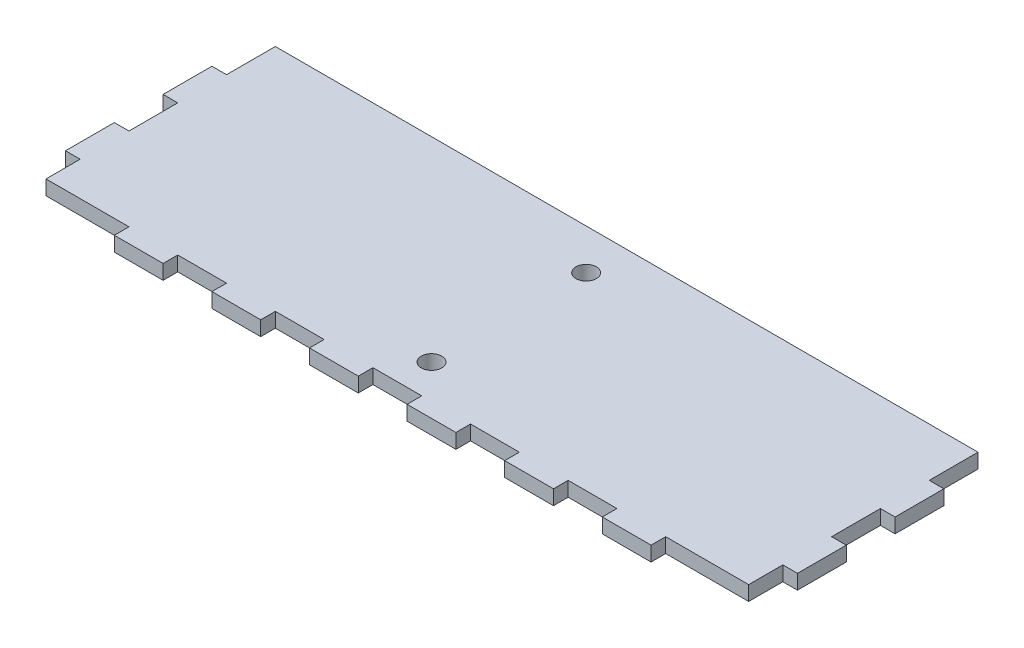
SolidWorks part; units mm, degrees
ref_plane "Plano frontal" through (0, 0, 0) normal (0, 0, 1) x (1, 0, 0)
ref_plane "Plano superior" through (0, 0, 0) normal (0, 1, 0) x (1, 0, 0)
ref_plane "Plano direito" through (0, 0, 0) normal (1, 0, 0) x (0, 0, -1)
sketch "mdfEsb" plane through (0, 0, 0) normal (0, 1, 0) x (1, 0, 0)
  line L1 (0, 0) -> (150, 0)
  line L2 (0, 0) -> (0, 50)
  line L3 (0, 50) -> (150, 50)
  line L4 (150, 0) -> (150, 50)
  dimension "D1" = 150
  dimension "D2" = 50
extrude "mdf" add sketch "mdfEsb" along normal blind 3
sketch "encaixeEsb" plane through (0, 3, 0) normal (0, 1, 0) x (1, 0, 0)
  line L0 (0, 0) -> (150, 0) construction
  line L1 (0, 0) -> (20, 0)
  line L2 (0, 0) -> (0, 3)
  line L4 (20, 0) -> (20, 3)
  line L5 (150, 0) -> (130, 0)
  line L6 (150, 0) -> (150, 3)
  line L8 (130, 0) -> (130, 3)
  line L9 (30, 0) -> (40, 0)
  line L10 (30, 0) -> (30, 3)
  line L11 (30, 3) -> (40, 3)
  line L12 (40, 0) -> (40, 3)
  line L13 (50, 0) -> (50, 3)
  line L14 (50, 0) -> (60, 0)
  line L15 (60, 0) -> (60, 3)
  line L16 (50, 3) -> (60, 3)
  line L17 (70, 0) -> (70, 3)
  line L18 (70, 0) -> (80, 0)
  line L19 (80, 0) -> (80, 3)
  line L20 (70, 3) -> (80, 3)
  line L21 (90, 0) -> (90, 3)
  line L22 (90, 0) -> (100, 0)
  line L23 (100, 0) -> (100, 3)
  line L24 (90, 3) -> (100, 3)
  line L25 (110, 0) -> (110, 3)
  line L26 (110, 0) -> (120, 0)
  line L27 (120, 0) -> (120, 3)
  line L28 (110, 3) -> (120, 3)
  line L29 (30, 0) -> (50, 0) construction
  line L30 (0, 50) -> (0, 0) construction
  line L31 (0, 20) -> (3, 20)
  line L32 (0, 20) -> (0, 30)
  line L33 (0, 30) -> (3, 30)
  line L34 (3, 20) -> (3, 30)
  line L35 (0, 40) -> (0, 50)
  line L36 (0, 40) -> (3, 40)
  line L37 (3, 40) -> (3, 50)
  line L38 (0, 50) -> (3, 50)
  line L39 (0, 60) -> (0, 70)
  line L40 (0, 60) -> (3, 60)
  line L41 (3, 60) -> (3, 70)
  line L42 (0, 70) -> (3, 70)
  line L43 (0, 80) -> (0, 90)
  line L44 (0, 80) -> (3, 80)
  line L45 (3, 80) -> (3, 90)
  line L46 (0, 90) -> (3, 90)
  line L47 (0, 100) -> (0, 110)
  line L48 (0, 100) -> (3, 100)
  line L49 (3, 100) -> (3, 110)
  line L50 (0, 110) -> (3, 110)
  line L51 (0, 20) -> (0, 40) construction
  line L52 (75, 0) -> (75, 100) construction
  line L53 (150, 20) -> (150, 40) construction
  line L54 (150, 110) -> (147, 110)
  line L55 (147, 100) -> (147, 110)
  line L56 (150, 100) -> (147, 100)
  line L57 (150, 100) -> (150, 110)
  line L58 (150, 90) -> (147, 90)
  line L59 (147, 80) -> (147, 90)
  line L60 (150, 80) -> (147, 80)
  line L61 (150, 80) -> (150, 90)
  line L62 (150, 70) -> (147, 70)
  line L63 (147, 60) -> (147, 70)
  line L64 (150, 60) -> (147, 60)
  line L65 (150, 60) -> (150, 70)
  line L66 (150, 50) -> (147, 50)
  line L67 (147, 40) -> (147, 50)
  line L68 (150, 40) -> (147, 40)
  line L69 (150, 40) -> (150, 50)
  line L70 (147, 20) -> (147, 30)
  line L71 (150, 30) -> (147, 30)
  line L72 (150, 20) -> (150, 30)
  line L73 (150, 20) -> (147, 20)
  line L74 (150, 0) -> (150, 50) construction
  line L75 (20, 3) -> (3, 3)
  line L76 (3, 3) -> (3, 10)
  line L77 (3, 10) -> (0, 10)
  line L78 (0, 10) -> (0, 3)
  line L79 (130, 3) -> (147, 3)
  line L80 (147, 3) -> (147, 10)
  line L81 (147, 10) -> (150, 10)
  line L82 (150, 10) -> (150, 3)
  dimension "D1" = 20
  dimension "D2" = 20
  dimension "D3" = 3
  dimension "D4" = 10
  dimension "D5" = 10
  dimension "D6" = 20
  dimension "D7" = 20
  dimension "D8" = 10
  dimension "D9" = 3
  dimension "D10" = 20
  dimension "D12" = 7
  dimension "D14" = 17
  dimension "D11" = 5
  dimension "D13" = 5
extrude "encaixe" cut sketch "encaixeEsb" against normal blind 3
sketch "USEsb" plane through (0, 3, 0) normal (0, 1, 0) x (1, 0, 0)
  line L0 (75, 50) -> (75, 3) construction
  line L1 (147, 50) -> (3, 50) construction
  line L2 (80, 3) -> (70, 3) construction
  line L3 (80, 0) -> (90, 0) construction
  circle A0 centre (75, 41.7) radius 2.1
  circle A1 centre (75, 10) radius 2.1
  dimension "D1" = 4.2
  dimension "D2" = 4.2
  dimension "D3" = 31.7
  dimension "D4" = 10
extrude "US" cut sketch "USEsb" against normal blind 3
